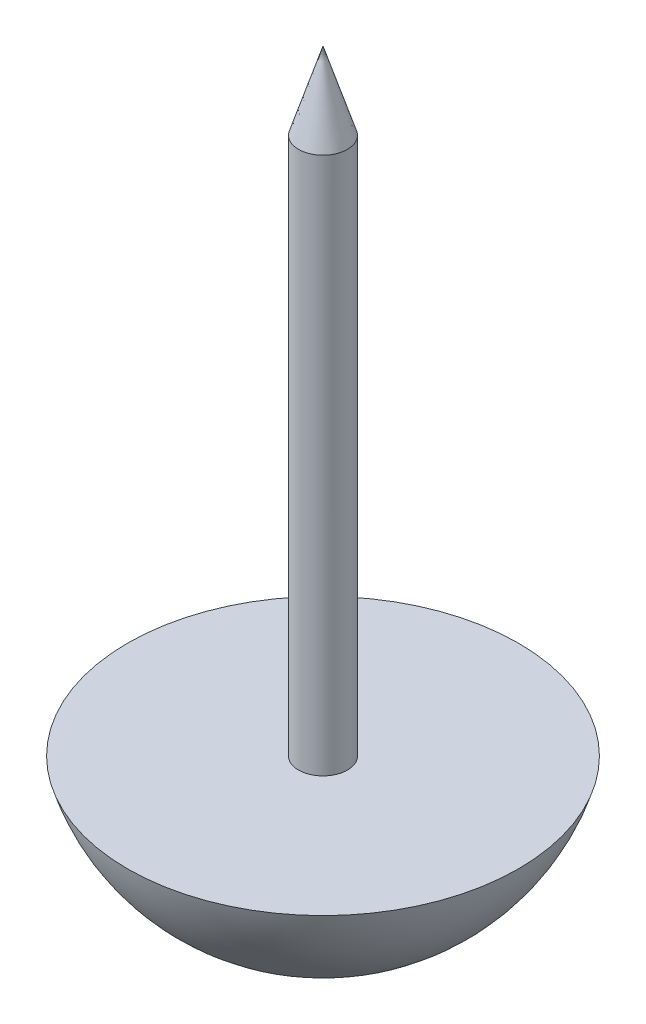
SolidWorks part; units mm, degrees
material "Delrin Acetal Copolymer (SS)"
ref_plane "Front" through (0, 0, 0) normal (0, 0, 1) x (1, 0, 0)
ref_plane "Top" through (0, 0, 0) normal (0, 1, 0) x (1, 0, 0)
ref_plane "Right" through (0, 0, 0) normal (1, 0, 0) x (0, 0, -1)
sketch "Sketch1" plane through (0, 0, 0) normal (1, 0, 0) x (0, 0, -1)
  line L0 (0, 26.7947) -> (0, -35.7263) construction
  line L1 (0, 19.9743) -> (0, -4.7625)
  line L2 (6.35, 0) -> (0.7938, 0)
  line L3 (0.7938, 0) -> (0.7938, 17.4625)
  line L4 (0.7938, 17.4625) -> (0, 19.9743)
  arc A0 (0, -4.7625) -> (6.35, 0) centre (0, 1.8521) ccw
  dimension "D1" = 12.7
  dimension "D2" = 1.5875
  dimension "D3" = 17.4625
  dimension "D4" = 4.7625
revolve "Revolve1" add sketch "Sketch1" angle 360 about L0
